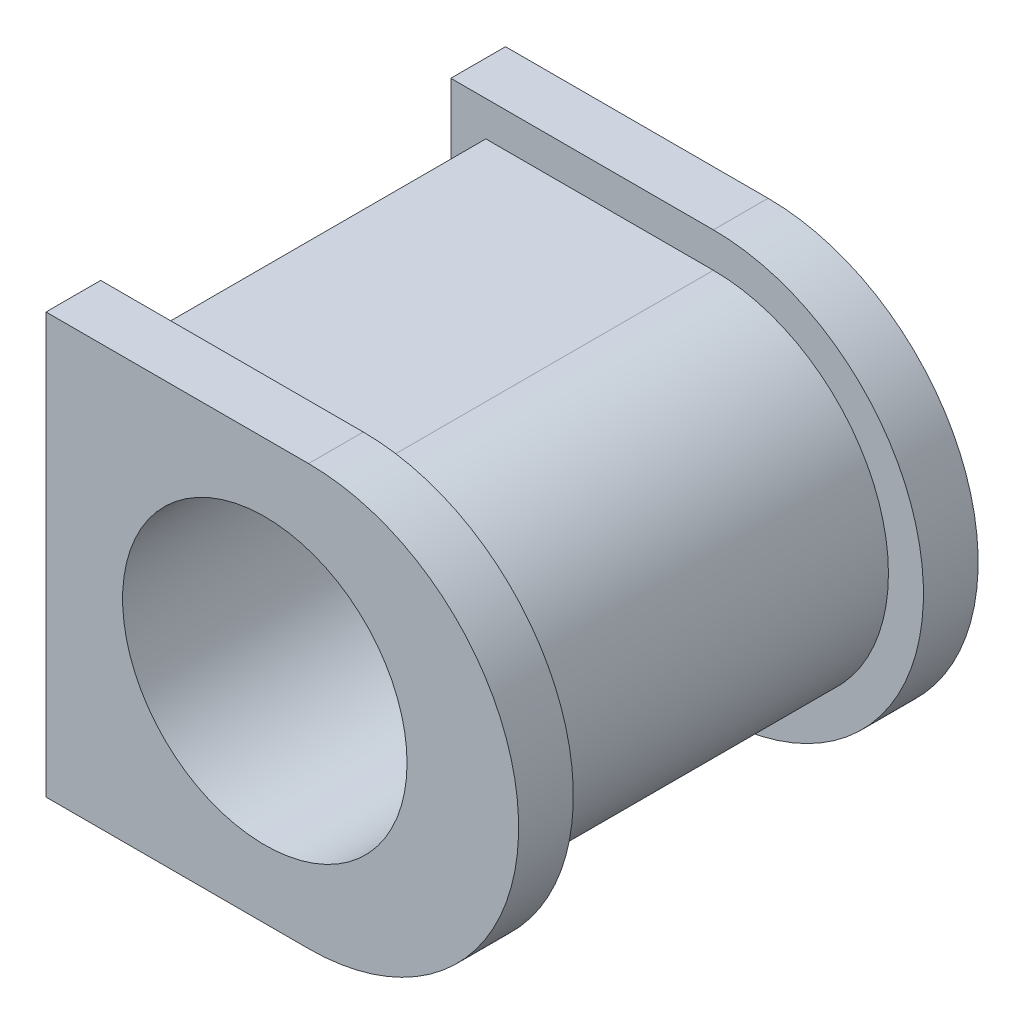
SolidWorks part; units mm, degrees
ref_plane "Front Plane" through (0, 0, 0) normal (0, 0, 1) x (1, 0, 0)
ref_plane "Top Plane" through (0, 0, 0) normal (0, 1, 0) x (1, 0, 0)
ref_plane "Right Plane" through (0, 0, 0) normal (1, 0, 0) x (0, 0, -1)
sketch "Sketch1" plane through (0, 0, 0) normal (0, 0, 1) x (1, 0, 0)
  line L1 (-26, -40) -> (26, -40)
  line L2 (-26, -40) -> (-26, 40)
  line L3 (-26, 40) -> (26, 40)
  line L5 (-26, -40) -> (-10.5554, -16.239) construction
  line L6 (-26, 40) -> (-10.5554, 16.239) construction
  line L7 (0, 0) -> (26, 40) construction
  arc A0 (26, -40) -> (26, 40) centre (26, 0) ccw
  circle A1 centre (16, 0) radius 32.5
  point P0 (0, 0)
  dimension "D3" = 80
  dimension "D4" = 80
  dimension "D5" = 65
  dimension "D1" = 52
  dimension "D2" = 80
  dimension "D6" = 10
extrude "Boss-Extrude1" add sketch "Sketch1" along normal mid plane 80
sketch "Sketch2" plane through (0, 0, 40) normal (0, 0, 1) x (1, 0, 0)
  line L9 (26, 48) -> (-34, 48)
  line L10 (-34, 48) -> (-34, -48)
  line L11 (-34, -48) -> (26, -48)
  line L12 (26, 48) -> (-34, 48)
  line L13 (-34, 48) -> (-34, -48)
  line L14 (-34, -48) -> (26, -48)
  circle A1 centre (16, 0) radius 32.5 construction
  circle A2 centre (16, 0) radius 32.5
  arc A5 (26, -48) -> (26, 48) centre (26, 0) ccw
  arc A6 (26, -48) -> (26, 48) centre (26, 0) ccw
  dimension "D1" = 8
extrude "Boss-Extrude2" add sketch "Sketch2" along normal blind 12.5
mirror "Mirror1" about plane through (0, 0, 0) normal (0, 0, 1) of "Boss-Extrude2"
